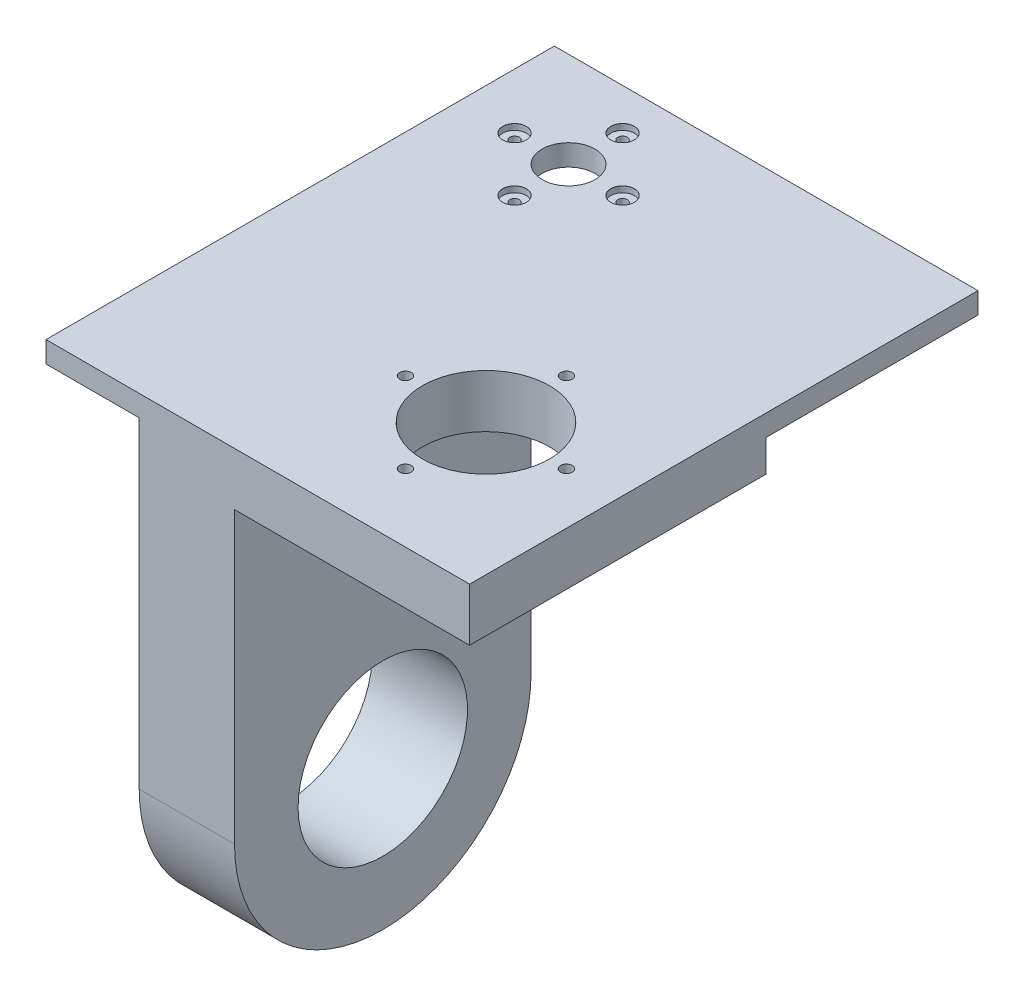
SolidWorks part; units mm, degrees
material "Acciaio al carbonio semplice"
ref_plane "Piano frontale" through (0, 0, 0) normal (0, 0, 1) x (1, 0, 0)
ref_plane "Piano superiore" through (0, 0, 0) normal (0, 1, 0) x (1, 0, 0)
ref_plane "Piano destro" through (0, 0, 0) normal (1, 0, 0) x (0, 0, -1)
sketch "Schizzo1" plane through (0, 0, 0) normal (1, 0, 0) x (0, 0, -1)
  line L0 (-826.3993, 0) -> (40493.5669, 0) construction
  line L1 (0, -826.3993) -> (0, 40493.5669) construction
  line L2 (-70, 0) -> (-70, 136.8)
  line L3 (-70, 136.8) -> (70, 136.8)
  line L4 (70, 136.8) -> (70, 0)
  circle A0 centre (0, 0) radius 40
  arc A1 (-70, 0) -> (70, 0) centre (0, 0) ccw
  dimension "D1" = 70
  dimension "D2" = 80
  dimension "D3" = 136.8
extrude "Estrusione-Estrusione1" add sketch "Schizzo1" along normal blind 45
sketch "Schizzo2" plane through (0, 136.8, 0) normal (0, 1, 0) x (1, 0, 0)
  line L0 (-1000, 0) -> (49000, 0) construction
  line L1 (93.7, -996.2442) -> (93.7, 49003.7558) construction
  line L6 (45, -70) -> (0, -70) construction
  line L7 (0, 70) -> (156, 70)
  line L8 (0, 70) -> (0, -70)
  line L9 (0, -70) -> (156, -70)
  line L10 (156, 70) -> (156, -70)
  circle A0 centre (93.7, 0) radius 30
  dimension "D1" = 93.7
  dimension "D2" = 156
  dimension "D3" = 60
extrude "Estrusione-Estrusione2" add sketch "Schizzo2" along normal blind 25
sketch "Schizzo5" plane through (0, 161.8, 0) normal (0, 1, 0) x (1, 0, 0)
  line L1 (0, -70) -> (-44, -70)
  line L2 (0, -70) -> (0, 70)
  line L3 (156, 170) -> (-44, 170)
  line L4 (-44, -70) -> (-44, 170)
  line L5 (-44, 170) -> (156, 170)
  line L6 (-44, 170) -> (-44, -70)
  line L7 (0, 70) -> (156, 70)
  line L8 (156, 170) -> (156, 70)
  line M8 (0, 70) -> (0, -70)
  line M11 (156, 70) -> (0, 70)
  dimension "D1" = 200
  dimension "D2" = 240
extrude "Estrusione-Estrusione4" add sketch "Schizzo5" against normal blind 10 contours L8 L3 L4 L1 M8 M11
sketch "Schizzo6" plane through (0, 161.8, 0) normal (0, 1, 0) x (1, 0, 0)
  circle A0 centre (7.7, 125) radius 12.5
  circle A1 centre (93.7, 0) radius 30 construction
  circle A2 centre (93.7, 0) radius 30 construction
  dimension "D1" = 25
  dimension "D2" = 125
  dimension "D3" = 86
extrude "Taglio-Estrusione1" cut sketch "Schizzo6" against normal blind 10
hole_wizard "Foro lamato per Vite M4 a testa esagonale-1" positions "Schizzo9" profile "Schizzo8" counterbore size "M4" standard "ISO" end condition through all
sketch "Schizzo9" plane through (0, 161.8, 0) normal (0, 1, 0) x (1, 0, 0)
  line L0 (7.7, -875) -> (7.7, 49125) construction
  line L1 (-992.3, 125) -> (49007.7, 125) construction
  circle A0 centre (7.7, 125) radius 12.5 construction
  circle A1 centre (7.7, 125) radius 12.5 construction
  point P0 (7.7, 150.5)
  point P2 (-17.8, 125)
  point P4 (7.7, 99.5)
  point P6 (33.2, 125)
  dimension "D1" = 25.5
  dimension "D2" = 25.5
  dimension "D3" = 25.5
  dimension "D4" = 25.5
sketch "Schizzo8" plane through (7.7, 161.8, -150.5) normal (1, 0, 0) x (0, 0, 1)
  line L0 (0, 0) -> (0, 231.8)
  line L1 (0, 231.8) -> (2.25, 231.8)
  line L3 (2.25, 231.8) -> (2.25, 2.8)
  line L4 (5.5415, 2.8) -> (2.25, 2.8)
  line L5 (5.5415, 2.8) -> (5.5415, 0.025)
  line L6 (5.5415, 0.025) -> (5.5665, 0)
  line L7 (5.5665, 0) -> (0, 0)
  line L8 (-5.5415, 0.025) -> (-5.5665, 0) construction
  line L11 (0, -6.35) -> (0, 107.95) construction
  dimension "Thru Hole Dia." = 4.5
  dimension "Thru Hole Depth" = 231.8
  dimension "C'Bore Dia." = 11.083
  dimension "C'Bore Depth" = 2.8
  dimension "Near C'Sink Dia." = 11.133
  dimension "Near C'Sink Angle" = 90
hole_wizard "Foro per Vite M5-1" positions "Schizzo10" profile "Schizzo11" hole size "M5" standard "ISO" end condition through all
sketch "Schizzo10" plane through (0, 161.8, 0) normal (0, 1, 0) x (1, 0, 0)
  line L0 (0, 0) -> (156, 0) construction
  line L1 (156, -70) -> (156, 170) construction
  line L5 (93.7, -30) -> (93.7, 30) construction
  circle A1 centre (93.7, 0) radius 30 construction
  point P0 (93.7, 38)
  point P2 (93.7, -38)
  point P4 (55.7, 0)
  point P6 (131.7, 0)
  point P29 (0, 0)
  point P30 (0, 0)
  point P31 (0, 0)
  point P32 (0, 0)
  dimension "D1" = 38
  dimension "D2" = 38
  dimension "D3" = 38
  dimension "D4" = 38
sketch "Schizzo11" plane through (93.7, 161.8, -38) normal (1, 0, 0) x (0, 0, 1)
  line L0 (0, 0) -> (0, 231.8)
  line L1 (0, 231.8) -> (2.75, 231.8)
  line L2 (2.75, 231.8) -> (2.75, 0)
  line L5 (2.75, 0) -> (0, 0)
  line L11 (0, -6.35) -> (0, 107.95) construction
  dimension "Thru Hole Dia." = 5.5
  dimension "Thru Hole Depth" = 231.8
